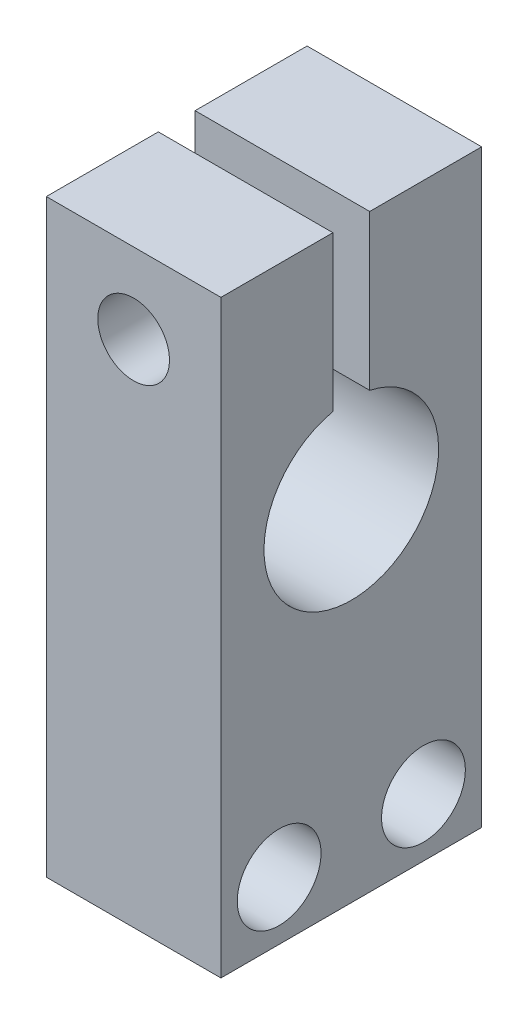
SolidWorks part; units mm, degrees
ref_plane "Front Plane" through (0, 0, 0) normal (0, 0, 1) x (1, 0, 0)
ref_plane "Top Plane" through (0, 0, 0) normal (0, 1, 0) x (1, 0, 0)
ref_plane "Right Plane" through (0, 0, 0) normal (1, 0, 0) x (0, 0, -1)
ref_plane "Plane1" through (4.7625, 0, 0) normal (1, 0, 0) x (0, 0, -1)
sketch "Sketch1" plane through (4.7625, 0, 0) normal (1, 0, 0) x (0, 0, -1)
  line L0 (15.875, -19.05) -> (15.875, 13.1064)
  line L1 (15.875, 13.1064) -> (-15.875, 13.1064)
  line L2 (-15.875, 13.1064) -> (-15.875, -19.05)
  line L3 (-15.875, -19.05) -> (15.875, -19.05)
  dimension "D1" = 31.75
  dimension "D2" = 32.1564
  dimension "D3" = 13.1064
  dimension "D4" = 15.875
extrude "Boss-Extrude1" add sketch "Sketch1" against normal blind 9.525
sketch "Sketch2" plane through (-4.7625, 0, 0) normal (-1, 0, 0) x (0, 0, 1)
  line L0 (-7.112, -19.05) -> (-7.112, 13.1064)
  line L1 (-7.112, 13.1064) -> (-15.875, 13.1064)
  line L2 (-15.875, 13.1064) -> (-15.875, -19.05)
  line L3 (-15.875, -19.05) -> (-7.112, -19.05)
  line L4 (15.875, -19.05) -> (-15.875, -19.05) construction
  line L5 (-15.875, 13.1064) -> (15.875, 13.1064) construction
  line L6 (-15.875, -19.05) -> (-15.875, 13.1064) construction
  dimension "D1" = 8.763
extrude "Cut-Extrude1" cut sketch "Sketch2" against normal through all
sketch "Sketch3" plane through (-4.7625, 0, 0) normal (-1, 0, 0) x (0, 0, 1)
  line L0 (1.0033, 13.1064) -> (-1.0033, 13.1064)
  line L1 (-1.0033, 13.1064) -> (-1.0033, 4.6556)
  line L2 (1.0033, 4.6556) -> (1.0033, 13.1064)
  line L3 (-7.112, -19.05) -> (-7.112, 13.1064) construction
  line L4 (-7.112, 13.1064) -> (15.875, 13.1064) construction
  arc A0 (-1.0033, 4.6556) -> (1.0033, 4.6556) centre (0, 0) cw
  dimension "D1" = 4.7625
  dimension "D2" = 6.1087
  dimension "D3" = 7.112
  dimension "D4" = 8.4508
extrude "Cut-Extrude2" cut sketch "Sketch3" against normal through all
sketch "Sketch4" plane through (-4.7625, 0, 0) normal (-1, 0, 0) x (0, 0, 1)
  line L0 (7.112, -19.0536) -> (15.875, -19.0536)
  line L1 (15.875, -19.0536) -> (15.875, 13.1064)
  line L2 (15.875, 13.1064) -> (7.112, 13.1064)
  line L3 (7.112, 13.1064) -> (7.112, -19.0536)
  line L4 (1.0033, 4.6556) -> (1.0033, 13.1064) construction
  line L5 (1.0033, 13.1064) -> (15.875, 13.1064) construction
  dimension "D1" = 6.1087
  dimension "D2" = 14.8717
  dimension "D3" = 32.16
extrude "Cut-Extrude3" cut sketch "Sketch4" against normal through all
sketch "Sketch5" plane through (0, 0, 0) normal (0, 0, 1) x (1, 0, 0)
  line L0 (-4.7625, 4.7625) -> (-4.7625, 0)
  line L1 (-4.7625, 0) -> (4.7625, 0)
  line L2 (4.7625, 0) -> (4.7625, 4.7625)
  line L3 (4.7625, 4.7625) -> (-4.7625, 4.7625)
  line L4 (-4.7625, 0) -> (4.7625, 0) construction
  dimension "D1" = 4.7625
  dimension "D2" = 4.7625
  dimension "D3" = 4.7625
revolve "Cut-Revolve1" cut sketch "Sketch5" angle 360 about L4
hole_wizard "Hole1" positions "Sketch7" profile "Sketch6" legacy
sketch "Sketch7" plane through (0, 0, 1.0033) normal (0, 0, -1) x (-1, 0, 0)
  point P0 (0, 8.7376)
sketch "Sketch6" plane through (0, 8.7376, 1.0033) normal (1, 0, 0) x (0, 1, 0)
  line L0 (0, 0) -> (0, 6.1087)
  line L1 (0, 6.1087) -> (1.3208, 6.1087)
  line L2 (1.3208, 6.1087) -> (1.3208, 0)
  line L3 (1.3208, 0) -> (0, 0)
  line L4 (0, 110) -> (0, -10) construction
  dimension "Diameter" = 2.6416
  dimension "Depth" = 6.1087
hole_wizard "CBORE for M3.5 Hex Head Machine Screw1" positions "Sketch9" profile "Sketch8" counterbore size "M3.5" standard "ANSI Metric"
sketch "Sketch9" plane through (0, 0, -7.112) normal (0, 0, -1) x (-1, 0, 0)
  point P0 (0, 8.7376)
sketch "Sketch8" plane through (0, 8.7376, -7.112) normal (1, 0, 0) x (0, 1, 0)
  line L0 (0, 0) -> (0, 14.224)
  line L1 (0, 14.224) -> (1.9558, 14.224)
  line L3 (1.9558, 14.224) -> (1.9558, 3.9116)
  line L4 (1.9558, 3.9116) -> (3.5687, 3.9116)
  line L5 (3.5687, 3.9116) -> (3.5687, 0)
  line L7 (3.5687, 0) -> (0, 0)
  line L11 (0, -6.35) -> (0, 107.95) construction
  dimension "Thru Hole Dia." = 3.9116
  dimension "Thru Hole Depth" = 14.224
  dimension "C'Bore Dia." = 7.1374
  dimension "C'Bore Depth" = 3.9116
hole_wizard "M4 Clearance Hole1" positions "Sketch11" profile "Sketch10" hole size "M4" standard "ANSI Metric"
sketch "Sketch11" plane through (4.7625, -17.4625, 0) normal (-1, 0, 0) x (0, 1, 0)
  line L3 (-1.5875, -7.112) -> (-1.5875, 7.112) construction
  line L4 (-1.5875, 7.112) -> (30.5689, 7.112) construction
  line L5 (30.5689, -7.112) -> (-1.5875, -7.112) construction
  point P2 (1.5875, 3.937)
  point P4 (1.5875, -3.937)
  dimension "D1" = 3.175
  dimension "D2" = 3.175
  dimension "D3" = 3.175
sketch "Sketch10" plane through (4.7625, -15.875, -3.937) normal (0, 1, 0) x (0, 0, -1)
  line L0 (0, 0) -> (0, 9.525)
  line L1 (0, 9.525) -> (2.286, 9.525)
  line L2 (2.286, 9.525) -> (2.286, 0)
  line L5 (2.286, 0) -> (0, 0)
  line L11 (0, -6.35) -> (0, 107.95) construction
  dimension "Thru Hole Dia." = 4.572
  dimension "Thru Hole Depth" = 9.525
